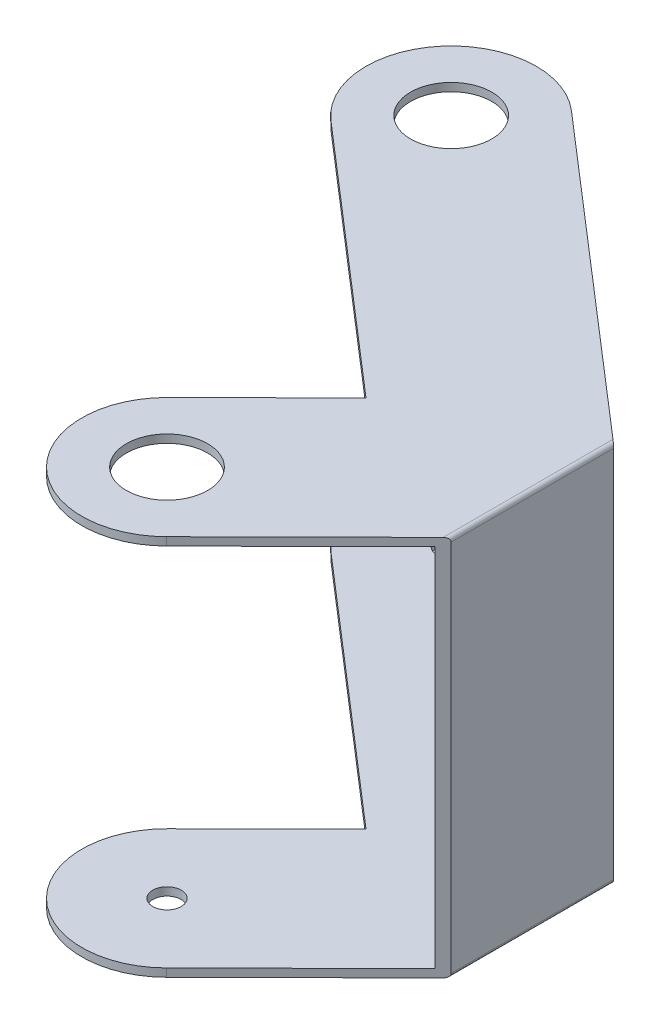
SolidWorks part; units mm, degrees
ref_plane "前视基准面" through (0, 0, 0) normal (0, 0, 1) x (1, 0, 0)
ref_plane "上视基准面" through (0, 0, 0) normal (0, 1, 0) x (1, 0, 0)
ref_plane "右视基准面" through (0, 0, 0) normal (1, 0, 0) x (0, 0, -1)
sketch "草图1" plane through (0, 0, 0) normal (0, 1, 0) x (1, 0, 0)
  line L0 (-40.0467, 0) -> (48.9586, 0) construction
  line L1 (0, 28.6211) -> (0, -29.5351) construction
  line L2 (-45.8336, 55) -> (67.8169, 55) construction
  line L3 (25, 30) -> (84.2704, 30) construction
  line L5 (25, 30) -> (-13.1358, 62.9456)
  line L6 (25, 10) -> (7.3926, -7.4565)
  line L7 (-26.8642, 47.0544) -> (4.8835, 19.6274)
  line L8 (-7.3926, 7.4565) -> (4.8835, 19.6274)
  line L10 (25, 30) -> (25, 10)
  arc A0 (-7.3926, 7.4565) -> (7.3926, -7.4565) centre (0, 0) ccw
  arc A1 (-13.1358, 62.9456) -> (-26.8642, 47.0544) centre (-20, 55) ccw
  dimension "D1" = 20
  dimension "D3" = 21
  dimension "D4" = 21
  dimension "D2" = 55
  dimension "D8" = 45
extrude "凸台-拉伸1" add sketch "草图1" along normal blind 47 contours L7 L8 A0 L6 L10 L5 A1
shell "抽壳1" thickness 1
fillet "圆角2" radius 0.5 2 edges at (25, 0, -20) (25, 47, -20)
hole_wizard "Ø10.0 (10) 直径槽口4" positions "草图4" profile "草图5" size "Ø10.0" standard "GB"
sketch "草图4" plane through (0, 47, 0) normal (0, 1, 0) x (1, 0, 0)
  line L0 (24.5, 30.432) -> (-13.1358, 62.9456) construction
  point P0 (0, 0)
  point P3 (-20, 55)
  dimension "D1" = 10.5
sketch "草图5" plane through (0, 47, 0) normal (1, 0, 0) x (0, 0, 1)
  line L0 (0, 0) -> (0, 1)
  line L1 (0, 1) -> (5, 1)
  line L2 (5, 1) -> (5, 0)
  line L5 (5, 0) -> (0, 0)
  line L11 (0, -6.35) -> (0, 107.95) construction
  dimension "通孔孔直径" = 10
  dimension "通孔孔深度" = 1
hole_wizard "Ø3.5 (3.5) 直径槽口1" positions "草图6" profile "草图7" size "Ø3.5" standard "GB" slot yes end condition up to next
sketch "草图6" plane through (0, 0, 0) normal (0, -1, 0) x (-1, 0, 0)
  line L2 (26.8642, 47.0544) -> (-4.8835, 19.6274) construction
  line L3 (-27.9177, 30) -> (-91.1625, 30) construction
  point P0 (0, 0)
  point P3 (20, 55)
  dimension "D1" = 25
  dimension "D2" = 10.5
sketch "草图7" plane through (0, 0, 0) normal (1, 0, 0) x (0, 0, -1)
  line L0 (0, 0) -> (0, 1)
  line L1 (0, 1) -> (1.75, 1)
  line L2 (1.75, 1) -> (1.75, 0)
  line L5 (1.75, 0) -> (0, 0)
  line L11 (0, -6.35) -> (0, 107.95) construction
  dimension "通孔孔直径" = 3.5
  dimension "通孔孔深度" = 1
